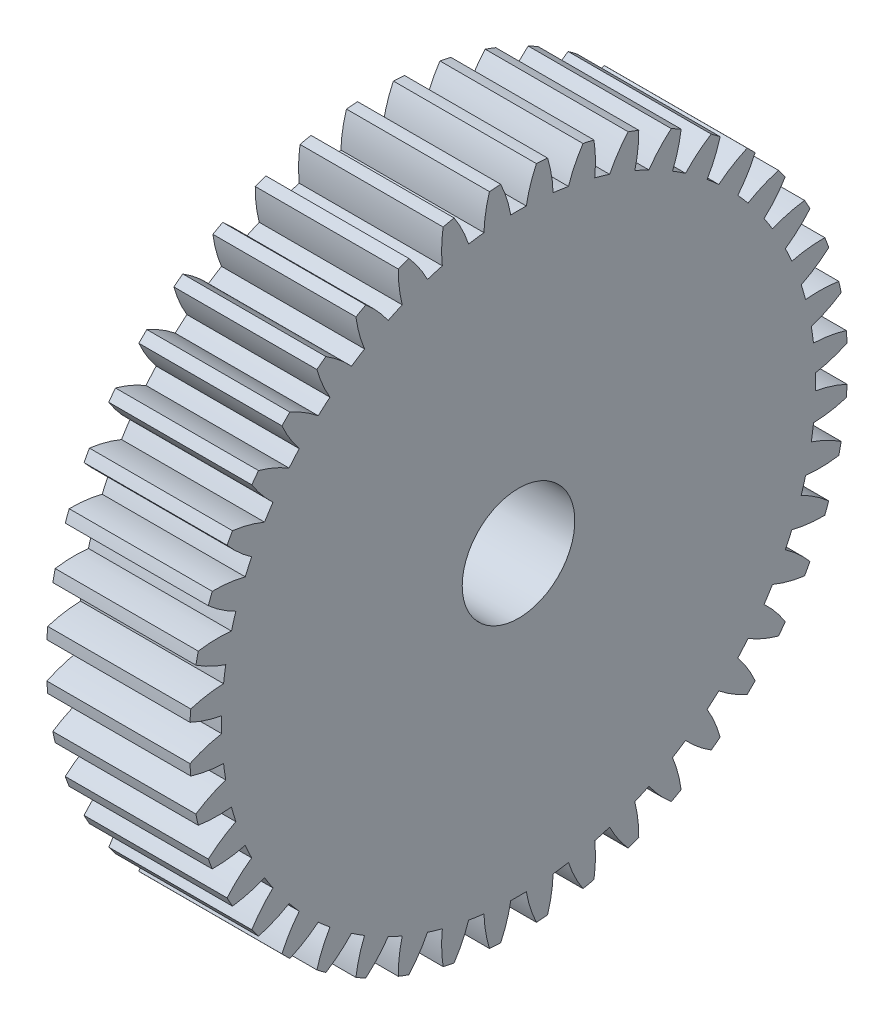
SolidWorks part; units mm, degrees
ref_plane "Plane1" through (0, 0, 0) normal (0, 0, 1) x (1, 0, 0)
ref_plane "Plane2" through (0, 0, 0) normal (0, 1, 0) x (1, 0, 0)
ref_plane "Plane3" through (0, 0, 0) normal (1, 0, 0) x (0, 0, -1)
other "Configuration Table"
sketch "HoldingSke" plane through (0, 0, 0) normal (0, 1, 0) x (1, 0, 0)
  line L0 (0, 0) -> (365.4246, -352.8865)
  line L1 (-15, 0) -> (100, 0) construction
  line L2 (0, 0) -> (-2.1039, 2.3779)
  line L3 (0, 0) -> (-11.863, 4.5341)
  line L4 (0, 0) -> (6.2122, 5.9991)
  line L5 (0, 0) -> (-47.5972, -17.7524)
  line L6 (0, 0) -> (-10.5278, -7.1032)
  line L7 (-2.1039, 2.3779) -> (8.8312, 51.9889)
  line L8 (-76.2, 54.61) -> (-74.168, 54.61)
  line L9 (-67.7845, 28.3722) -> (-49.3413, 33.142)
  line L10 (-76.2, 71.12) -> (104.1128, 71.12)
  line L11 (0, 0) -> (-12.7, 0)
  line L12 (-76.2, 101.6) -> (-76.1492, 101.6)
  line L13 (24.9733, 27.94) -> (52.9518, 28.4284)
  line L14 (24.9733, 27.94) -> (25.0241, 27.9398)
  line L15 (24.9733, 27.94) -> (100.4021, 29.52)
  circle A0 centre (0, 0) radius 5
  circle A1 centre (0, 0) radius 26.3652
  circle A2 centre (0, 0) radius 38.1
  circle A3 centre (0, 0) radius 5
  dimension "MHD" = 52.7304
  dimension "Hub_dia" = 76.2
  dimension "Bore" = 10
  dimension "MBD" = 10
  dimension "Num_teeth" = 44
  dimension "Pitch" = 508
  dimension "Overall_len" = 50.8
  dimension "Show_teeth" = 44
  dimension "Thickness" = 12.7
  dimension "OAL" = 50.8019
  dimension "T_dim" = 2.032
  dimension "Ap" = 14.5
  dimension "H" = 19.05
  dimension "Pitch_radius" = 180.3128
  dimension "Width" = 12.7
  dimension "Backlash" = 0.0508
  dimension "Addendum_fac" = 1
  dimension "Dedendum_fac" = 1.2
  dimension "Clearance_fac" = 0.2
  dimension "Dedendum_add" = 0.0508
sketch "BasProSke" plane through (0, 0, 0) normal (0, 1, 0) x (1, 0, 0)
  line L0 (-10, 0) -> (60, 0) construction
  line L1 (0, 0) -> (0, 29.21)
  line L2 (0, 0) -> (12.7, 0)
  line L3 (12.7, 0) -> (12.7, 29.21)
  line L4 (12.7, 29.21) -> (0, 29.21)
  dimension "Thickness" = 12.7
  dimension "Diameter" = 58.42
revolve "Base-Revolve" add sketch "BasProSke" angle 360 about L0
sketch "TooCutSke" plane through (0, 0, 0) normal (1, 0, 0) x (0, 0, -1)
  line L1 (0, 0) -> (0, 107) construction
  line L2 (0, 0) -> (-1.0861, 27.9189) construction
  line L3 (0, 0) -> (-3.9843, 55.7082) construction
  line L4 (-1.0861, 27.9189) -> (-1.9922, 27.8541) construction
  arc A0 (0.6891, 26.3562) -> (-0.6891, 26.3562) centre (0, 0) ccw
  arc A1 (1.598, 29.1917) -> (-1.598, 29.1917) centre (0, 0) ccw
  circle A2 centre (0, 0) radius 27.94 construction
  circle A3 centre (0, 0) radius 27.05 construction
  arc A4 (-0.6891, 26.3562) -> (-1.598, 29.1917) centre (-11.6914, 24.393) ccw
  arc A5 (1.598, 29.1917) -> (0.6891, 26.3562) centre (11.6914, 24.393) ccw
  dimension "Root_dia" = 52.7304
  dimension "Overcut_dia" = 58.4708
  dimension "Pitch_dia" = 55.88
  dimension "Base_dia" = 54.1001
  dimension "Flank_rad" = 11.176
  dimension "Half_ang" = 4.091
  dimension "Half_CT" = 0.9083
extrude "ToothCut" cut sketch "TooCutSke" along normal through all
fillet "Breaks" [suppressed] radius 0.0254
fillet "RootFillets" [suppressed] radius 0.3048
pattern_circular "TeethCuts" count 44 every 8.182 about axis through (-10, 0, 0) along (1, 0, 0) of "ToothCut", "RootFillets", "Breaks"
sketch "HubNeaOneSke" plane through (0, 0, 0) normal (-1, 0, 0) x (0, 0, 1)
  circle A0 centre (0, 0) radius 26.3652
  dimension "Diameter" = 52.7304
extrude "HubNearOne" [suppressed] add sketch "HubNeaOneSke" along normal blind 38.1019
sketch "HubNeaBotSke" plane through (0, 0, 0) normal (-1, 0, 0) x (0, 0, 1)
  circle A0 centre (0, 0) radius 26.3652
  dimension "Diameter" = 52.7304
extrude "HubNearBoth" [suppressed] add sketch "HubNeaBotSke" along normal blind 19.0509
ref_plane "FarPln" through (12.7, 0, 0) normal (1, 0, 0) x (0, 0, -1)
sketch "HubFarSke" plane through (12.7, 0, 0) normal (1, 0, 0) x (0, 0, -1)
  circle A0 centre (0, 0) radius 26.3652
  dimension "Diameter" = 52.7304
extrude "HubFar" [suppressed] add sketch "HubFarSke" along normal blind 19.0509
sketch "BorSke" plane through (0, 0, 0) normal (1, 0, 0) x (0, 0, -1)
  circle A0 centre (0, 0) radius 5
  dimension "Diameter" = 10
extrude "Bore" cut sketch "BorSke" along normal mid plane 101.6038
sketch "KeySke" plane through (0, 0, 0) normal (1, 0, 0) x (0, 0, -1)
  line L0 (-0.127, 0) -> (-0.127, 2.968)
  line L1 (-0.127, 2.968) -> (0.127, 2.968)
  line L2 (0.127, 2.968) -> (0.127, 0)
  line L3 (0, 0) -> (0, 34) construction
  line L4 (-0.127, 0) -> (0.127, 0)
  dimension "Offset" = 2.968
  dimension "Width" = 0.254
extrude "Keyway" [suppressed] cut sketch "KeySke" along normal mid plane 101.6038
pattern_circular "Keyway2" [suppressed] count 2 every 90 about axis through (-10, 0, 0) along (1, 0, 0)
sketch "Sketch1" plane through (0, 0, 0) normal (-1, 0, 0) x (0, 0, 1)
  circle A0 centre (0, 0) radius 7.5
  circle A1 centre (0, 0) radius 1.4999
  dimension "D1" = 15
  dimension "D2" = 2.9997
extrude "Boss-Extrude1" add sketch "Sketch1" along normal blind 5.5 and the other way blind 1.27
sketch "Sketch2" plane through (-5.5, 0, 0) normal (-1, 0, 0) x (0, 0, 1)
  circle A0 centre (0, 0) radius 2.875
  dimension "D1" = 5.75
extrude "Cut-Extrude1" cut sketch "Sketch2" against normal blind 3 and the other way through all
fillet "Fillet1" radius 5.08 1 edges at (0, 0, -7.5)
equation "' \"Pitch@HoldingSke\" = 4"
equation "' \"Num_teeth@HoldingSke\" = 12"
equation "' \"Ap@HoldingSke\" =  20"
equation "' \"Ap@HoldingSke\" = 20"
equation "' \"Width@HoldingSke\" = 0.5"
equation "' \"Hub_dia@HoldingSke\"= 1"
equation "' \"Hub_dia@HoldingSke\" = 1"
equation "' \"Overall_len@HoldingSke\" = 1.0"
equation "' \"Bore@HoldingSke\" = 0.75"
equation "' \"T_dim@HoldingSke\" = 0.85"
equation "' \"Width@KeySke\" = 0.25"
equation "' \"Show_teeth@HoldingSke\" = 13"
equation "' \"Backlash@HoldingSke\" = 0.009"
equation "' \"Addendum_fac@HoldingSke\" = 1.0"
equation "' \"Dedendum_fac@HoldingSke\" = 1.25"
equation "' \"Dedendum_add@HoldingSke\" = 0.00005"
equation "' \"Clearance_fac@HoldingSke\" = 0.25"
equation "' \"Pitch@HoldingSke\" = 0.5"
equation "' \"Num_teeth@HoldingSke\" = 23"
equation "' \"Show_teeth@HoldingSke\" = 23"
equation "' \"Backlash@HoldingSke\" = 0.0375"
equation "\"Overcut_dia@TooCutSke\" = (\"Num_teeth@HoldingSke\" + 2 * \"Addendum_fac@HoldingSke\") / \"Pitch@HoldingSke\" + 0.002"
equation "\"Pitch_dia@TooCutSke\" = \"Num_teeth@HoldingSke\" / \"Pitch@HoldingSke\""
equation "\"Base_dia@TooCutSke\" = \"Num_teeth@HoldingSke\" / \"Pitch@HoldingSke\" * cos((\"Ap@HoldingSke\"  * 3.14159265 / 180))"
equation "\"Root_dia@TooCutSke\" = (\"Num_teeth@HoldingSke\" + 2) / \"Pitch@HoldingSke\" - 2 * (\"Addendum_fac@HoldingSke\" + \"Dedendum_fac@HoldingSke\") / \"Pitch@HoldingSke\" - \"Dedendum_add@HoldingSke\" * 2"
equation "\"Half_ang@TooCutSke\" = 180 / \"Num_teeth@HoldingSke\""
equation "\"Half_CT@TooCutSke\" = \"Num_teeth@HoldingSke\" / \"Pitch@HoldingSke\" * sin((3.14159265 / 2 / \"Num_teeth@HoldingSke\")) / 2 - 7 * \"Backlash@HoldingSke\" / 4"
equation "\"Flank_rad@TooCutSke\" = \"Num_teeth@HoldingSke\" / \"Pitch@HoldingSke\" / 5"
equation "\"Radius@RootFillets\" = \"Clearance_fac@HoldingSke\" / \"Pitch@HoldingSke\" + \"Dedendum_add@HoldingSke\""
equation "\"Break_rad@Breaks\" = 0.02 / \"Pitch@HoldingSke\""
equation "\"Thickness@HoldingSke\" = \"Width@HoldingSke\""
equation "\"OAL@HoldingSke\" = \"Thickness@HoldingSke\""
equation "\"MHD@HoldingSke\" = (\"Num_teeth@HoldingSke\" + 2) / \"Pitch@HoldingSke\" - 2 * (\"Addendum_fac@HoldingSke\" + \"Dedendum_fac@HoldingSke\")  / \"Pitch@HoldingSke\" - \"Dedendum_add@HoldingSke\" * 2"
equation "\"MBD@HoldingSke\" = (\"Num_teeth@HoldingSke\" + 2) / \"Pitch@HoldingSke\" - 2 * (\"Addendum_fac@HoldingSke\" + \"Dedendum_fac@HoldingSke\")  / \"Pitch@HoldingSke\" - \"Dedendum_add@HoldingSke\" * 2 - 0.002"
equation "\"MHD@HoldingSke\" = ((sgn( \"MHD@HoldingSke\" - \"Hub_dia@HoldingSke\" )-1)*( \"MHD@HoldingSke\" - \"Hub_dia@HoldingSke\" ))/-2+ \"Hub_dia@HoldingSke\""
equation "\"MBD@HoldingSke\"=((sgn( \"MBD@HoldingSke\" - \"Bore@HoldingSke\" )+1)*( \"MBD@HoldingSke\" - \"Bore@HoldingSke\" ))/-2+ \"Bore@HoldingSke\""
equation "\"OAL@HoldingSke\" = ((sgn( \"OAL@HoldingSke\" - \"Overall_len@HoldingSke\" )+1)*( \"OAL@HoldingSke\" - \"Overall_len@HoldingSke\" ))/2 + \"Overall_len@HoldingSke\" + 0.000002"
equation "\"Num_teeth@TeethCuts\" = int( \"Show_teeth@HoldingSke\" ) + 1"
equation "\"Num_teeth@TeethCuts\" = ((sgn( \"Num_teeth@TeethCuts\" - \"Num_teeth@HoldingSke\" )-1)*( \"Num_teeth@TeethCuts\" - \"Num_teeth@HoldingSke\" ))/-2+ \"Num_teeth@HoldingSke\""
equation "\"Num_teeth@TeethCuts\" = ((sgn( \"Num_teeth@TeethCuts\" - 2.0)+1)*( \"Num_teeth@TeethCuts\" - 2.0))/2 +2.0"
equation "\"Angle@TeethCuts\" = 360.0 / \"Num_teeth@HoldingSke\""
equation "\"Diameter@BasProSke\" = (\"Num_teeth@HoldingSke\" + 2 * \"Addendum_fac@HoldingSke\") / \"Pitch@HoldingSke\""
equation "\"Thickness@BasProSke\"  = \"Thickness@HoldingSke\""
equation "' \"Fillet_rad@BasProSke\" =  \"Thickness@HoldingSke\" * 0.05"
equation "' \"Fillet_rad@BasProSke\" = \"Thickness@HoldingSke\" * 0.05"
equation "\"MHD@HoldingSke\" = ((sgn( \"MHD@HoldingSke\" - \"Root_dia@TooCutSke\" )-1)*( \"MHD@HoldingSke\" - \"Root_dia@TooCutSke\" ))/-2+ \"Root_dia@TooCutSke\""
equation "\"Diameter@HubNeaOneSke\" = \"MHD@HoldingSke\""
equation "\"Length@HubNearOne\" = \"OAL@HoldingSke\" - \"Thickness@BasProSke\""
equation "\"Diameter@HubNeaBotSke\" = \"MHD@HoldingSke\""
equation "\"Length@HubNearBoth\" = ( \"OAL@HoldingSke\" - \"Thickness@BasProSke\" ) / 2.0"
equation "\"Thickness@FarPln\" = \"Thickness@BasProSke\""
equation "\"Diameter@HubFarSke\" = \"MHD@HoldingSke\""
equation "\"Length@HubFar\" = ( \"OAL@HoldingSke\" - \"Thickness@BasProSke\" ) / 2.0"
equation "\"Diameter@BorSke\"=\"MBD@HoldingSke\""
equation "\"D1@Bore\" = \"OAL@HoldingSke\" * 2.0"
equation "\"D1@Keyway\" = \"OAL@HoldingSke\" * 2.0"
equation "\"Offset@KeySke\" = \"T_dim@HoldingSke\" - \"MBD@HoldingSke\" / 2.0"
